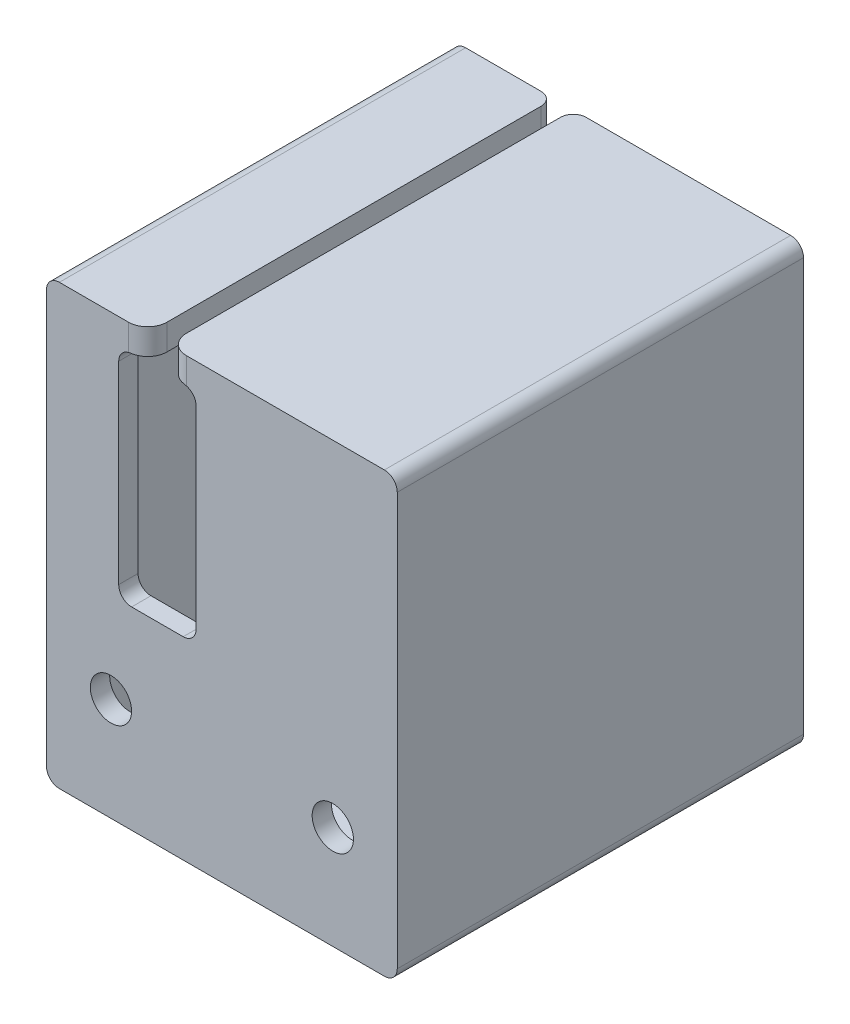
SolidWorks part; units mm, degrees
ref_plane "Front Plane" through (0, 0, 0) normal (0, 0, 1) x (1, 0, 0)
ref_plane "Top Plane" through (0, 0, 0) normal (0, 1, 0) x (1, 0, 0)
ref_plane "Right Plane" through (0, 0, 0) normal (1, 0, 0) x (0, 0, -1)
sketch "Sketch1" plane through (0, 0, 0) normal (0, 0, 1) x (1, 0, 0)
  line L1 (11.6, 15) -> (-11.6, 15)
  line L2 (11.6, 15) -> (11.6, -15)
  line L3 (11.6, -15) -> (-11.6, -15)
  line L4 (-11.6, 15) -> (-11.6, -15)
  line L5 (11.6, 15) -> (-11.6, -15) construction
  line L6 (11.6, -15) -> (-11.6, 15) construction
  line L7 (13.6, 17) -> (-13.6, 17)
  line L8 (13.6, 17) -> (13.6, -17)
  line L9 (13.6, -17) -> (-13.6, -17)
  line L10 (-13.6, 17) -> (-13.6, -17)
  line L11 (13.6, 17) -> (-13.6, -17) construction
  line L12 (13.6, -17) -> (-13.6, 17) construction
  point P0 (0, 0)
  point P6 (0, 0)
  dimension "D1" = 23.2
  dimension "D2" = 30
  dimension "D3" = 2
  dimension "D4" = 2
extrude "Boss-Extrude1" add sketch "Sketch1" along normal blind 30
sketch "Sketch2" plane through (0, 0, 30) normal (0, 0, 1) x (1, 0, 0)
  line L1 (13.6, 17) -> (-13.6, 17)
  line L2 (13.6, 17) -> (13.6, -17)
  line L3 (13.6, -17) -> (-13.6, -17)
  line L4 (-13.6, 17) -> (-13.6, -17)
  line L5 (13.6, 17) -> (-13.6, -17) construction
  line L6 (13.6, -17) -> (-13.6, 17) construction
  point P0 (0, 0)
extrude "Boss-Extrude2" add sketch "Sketch2" along normal blind 1.5
sketch "Sketch3" plane through (0, 0, 31.5) normal (0, 0, 1) x (1, 0, 0)
  line L0 (-13.6, 15) -> (13.6, 15) construction
  line L1 (-13.6, 17) -> (-13.6, -17) construction
  line L2 (13.6, -17) -> (13.6, 17) construction
  line L3 (13.6, 17) -> (-13.6, 17) construction
  line L4 (-13.6, -2) -> (2.1, -2)
  line L5 (2.1, -2) -> (2.1, 15)
  line L7 (-12.1, -2) -> (-12.1, 15)
  line L8 (-5, -2) -> (-5, 15) construction
  line L9 (-8.6, -9) -> (8.6, -9) construction
  line L10 (-2, 15) -> (-8, 15)
  line L11 (-2, 15) -> (-2, -2)
  line L12 (-2, -2) -> (-8, -2)
  line L13 (-8, 15) -> (-8, -2)
  line L14 (-2, 15) -> (-8, -2) construction
  line L15 (-2, -2) -> (-8, 15) construction
  line L16 (-13.6, -17) -> (13.6, -17) construction
  circle A0 centre (-8.6, -9) radius 1.6
  circle A3 centre (8.6, -9) radius 1.6
  point P9 (-5, 6.5)
  dimension "D6" = 3.2
  dimension "D9" = 5
  dimension "D1" = 2
  dimension "D2" = 17
  dimension "D3" = 11.5
  dimension "D4" = 1.5
  dimension "D5" = 6
  dimension "D7" = 8
  dimension "D8" = 5
extrude "Cut-Extrude1" cut sketch "Sketch3" against normal up to surface (31.5 mm away) contours L10 L13 L4 L11 | A0 | A3 up to face at (0, 0, 0)
fillet "Fillet1" radius 1 8 edges at (-2, -2, 30.75) (-8, -2, 30.75) (-8, 15, 30.75) (-2, 15, 30.75) (13.6, 17, 15.75) (-13.6, 17, 15.75) (13.6, -17, 15.75) (-13.6, -17, 15.75)
sketch "Sketch4" plane through (0, 0, 31.5) normal (0, 0, 1) x (1, 0, 0)
  line L0 (-5, 15) -> (-5, 17) construction
  line L1 (-3, 15) -> (-7, 15) construction
  line L2 (12.6, 17) -> (-12.6, 17) construction
  line L4 (-4.25, 17) -> (-5.75, 17)
  line L5 (-4.25, 17) -> (-4.25, 15)
  line L6 (-4.25, 15) -> (-5.75, 15)
  line L7 (-5.75, 17) -> (-5.75, 15)
  line L8 (-4.25, 17) -> (-5.75, 15) construction
  line L9 (-4.25, 15) -> (-5.75, 17) construction
  point P6 (-5, 16)
  dimension "D1" = 1.5
extrude "Cut-Extrude2" cut sketch "Sketch4" against normal up to surface (31.5 mm away) up to face at (0, 0, 0)
fillet "Fillet2" radius 1 2 edges at (-4.25, 16, 0) (-5.75, 16, 0)
fillet "Fillet3" radius 1.5 2 edges at (-5.75, 16, 31.5) (-4.25, 16, 31.5)
